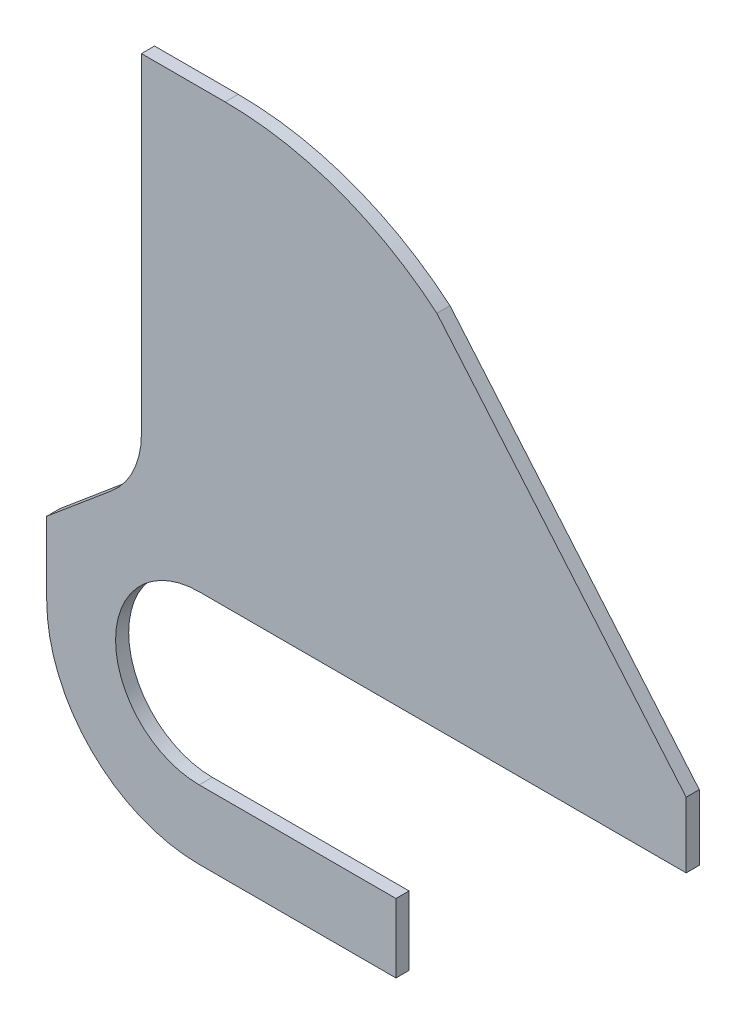
SolidWorks part; units mm, degrees
ref_plane "前视基准面" through (0, 0, 0) normal (0, 0, 1) x (1, 0, 0)
ref_plane "上视基准面" through (0, 0, 0) normal (0, 1, 0) x (1, 0, 0)
ref_plane "右视基准面" through (0, 0, 0) normal (1, 0, 0) x (0, 0, -1)
sketch "草图1" plane through (0, 0, 0) normal (0, 0, 1) x (1, 0, 0)
  line L0 (-692.3681, 756.238) -> (-692.3681, 714.238)
  line L1 (-812.3681, 714.238) -> (-692.3681, 714.238)
  line L2 (-905.3681, 807.238) -> (-905.3681, 851.6505)
  line L3 (-847.6193, 1124.8891) -> (-796.6193, 1124.8891)
  line L5 (-905.3681, 851.6505) -> (-865.8372, 884.8209)
  line L6 (-847.6193, 923.8891) -> (-847.6193, 1124.8891)
  line L7 (-692.3681, 756.238) -> (-812.3681, 756.238)
  line L31 (-812.3681, 858.238) -> (-515.3681, 858.238)
  line L34 (-515.3681, 858.238) -> (-515.3681, 898.238)
  line L35 (-667.419, 1077.8641) -> (-515.3681, 898.238)
  arc A0 (-812.3681, 714.238) -> (-905.3681, 807.238) centre (-812.3681, 807.238) cw
  arc A1 (-847.6193, 923.8891) -> (-865.8372, 884.8209) centre (-898.6193, 923.8891) cw
  arc A2 (-812.3681, 714.238) -> (-812.3681, 900.238) centre (-812.3681, 807.238) cw construction
  arc A3 (-812.3681, 756.238) -> (-812.3681, 858.238) centre (-812.3681, 807.238) cw
  arc A9 (-667.419, 1077.8641) -> (-796.6193, 1124.8891) centre (-796.6193, 923.8891) ccw
  point P61 (-847.6193, 1124.8891)
  dimension "D2" = 42
extrude "凸台-拉伸1" add sketch "草图1" along normal mid plane 8
